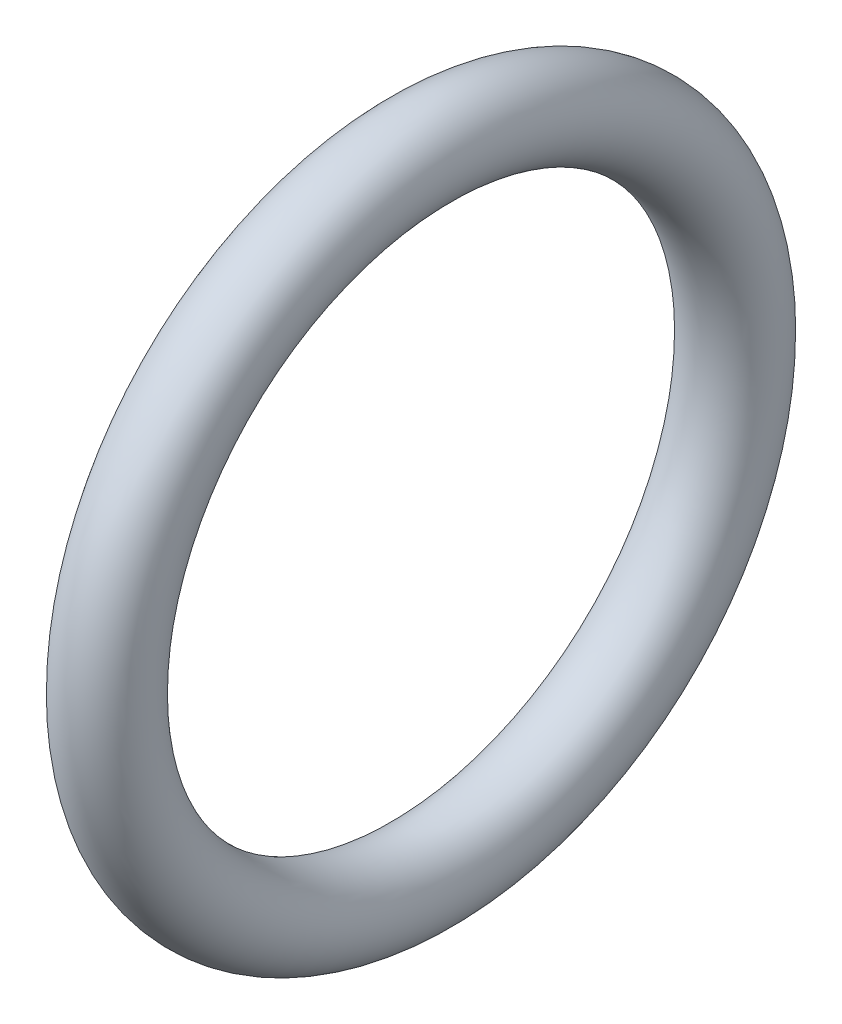
SolidWorks part; units mm, degrees
ref_plane "Спереди" through (0, 0, 0) normal (0, 0, 1) x (1, 0, 0)
ref_plane "Сверху" through (0, 0, 0) normal (0, 1, 0) x (1, 0, 0)
ref_plane "Справа" through (0, 0, 0) normal (1, 0, 0) x (0, 0, -1)
sketch "Эскиз1" plane through (0, 0, 0) normal (0, 0, 1) x (1, 0, 0)
  line L0 (-17.8043, -66) -> (41.0138, -66) construction
  circle A0 centre (0, 0) radius 9
  dimension "D1" = 18
  dimension "D2" = 66
revolve "Повернуть1" add sketch "Эскиз1" angle 360 about L0
